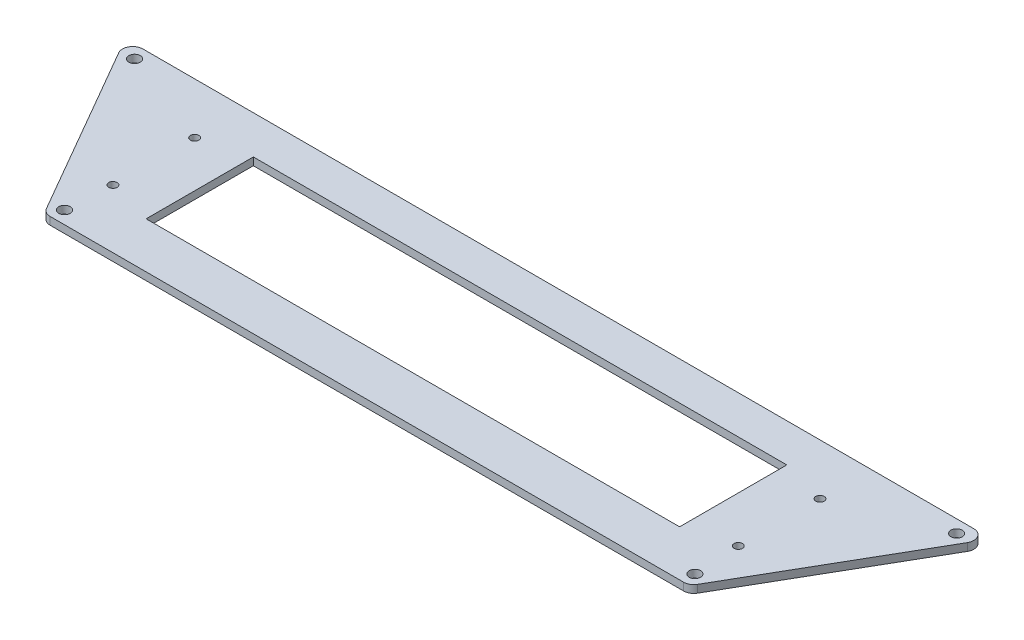
SolidWorks part; units mm, degrees
material "6061 合金"
ref_plane "前视基准面" through (0, 0, 0) normal (0, 0, 1) x (1, 0, 0)
ref_plane "上视基准面" through (0, 0, 0) normal (0, 1, 0) x (1, 0, 0)
ref_plane "右视基准面" through (0, 0, 0) normal (1, 0, 0) x (0, 0, -1)
sketch "草图1" plane through (0, 0, 0) normal (0, 1, 0) x (1, 0, 0)
  line L0 (0, 0) -> (0, 85.8862) construction
  line L1 (-169.688, 36) -> (-126.3868, -39)
  line L2 (-126.3868, -39) -> (126.3868, -39)
  line L3 (169.688, 36) -> (126.3868, -39)
  line L4 (-169.688, 36) -> (169.688, 36)
  line L6 (-161.0278, 31) -> (161.0278, 31) construction
  line L7 (-161.0278, 31) -> (-123.5, -34) construction
  line L8 (-123.5, -34) -> (123.5, -34) construction
  line L9 (161.0278, 31) -> (123.5, -34) construction
  line L10 (-161.0278, 31) -> (123.5, -34) construction
  line L11 (-123.5, -34) -> (161.0278, 31) construction
  line L12 (-122.5, -16) -> (122.5, -16) construction
  line L13 (-122.5, -16) -> (-122.5, 16) construction
  line L14 (-122.5, 16) -> (122.5, 16) construction
  line L15 (122.5, -16) -> (122.5, 16) construction
  line L16 (-122.5, -16) -> (122.5, 16) construction
  line L17 (-122.5, 16) -> (122.5, -16) construction
  point P6 (0, -5.7866)
  dimension "D2" = 5
  dimension "D1" = 15
  dimension "D4" = 247
  dimension "D6" = 32
  dimension "D7" = 245
  dimension "D8" = 18
  dimension "D9" = 120
extrude "凸台-拉伸1" add sketch "草图1" along normal blind 3
hole_wizard "M4 螺纹孔1" positions "草图3" profile "草图2" tap size "M4" standard "GB"
sketch "草图3" plane through (0, 3, 0) normal (0, 1, 0) x (1, 0, 0)
  line L0 (0, 0) -> (0, 124.5937) construction
  point P14 (122.5, 16)
  point P17 (-122.5, -16)
  point P18 (-122.5, 16)
  point P19 (122.5, -16)
sketch "草图2" plane through (122.5, 3, -16) normal (1, 0, 0) x (0, 0, 1)
  line L0 (0, 0) -> (0, 12.4914)
  line L1 (0, 12.4914) -> (1.65, 11.5)
  line L2 (1.65, 11.5) -> (1.65, 0)
  line L5 (1.65, 0) -> (0, 0)
  line L10 (0, 12.4914) -> (-1.65, 11.5) construction
  line L11 (0, -6.35) -> (0, 107.95) construction
  dimension "螺纹孔钻头直径" = 3.3
  dimension "螺纹孔钻头深度" = 11.5
  dimension "导头角度" = 118
cosmetic thread "孔螺蚊线1" parameters "D1"=4, "D2"=4
cosmetic thread "孔螺蚊线3" parameters "D1"=4, "D2"=4
cosmetic thread "孔螺蚊线4" parameters "D1"=4, "D2"=4
cosmetic thread "孔螺蚊线5" parameters "D1"=4, "D2"=4
hole_wizard "M4 间隙孔2" positions "草图8" profile "草图7" hole size "M4" standard "GB"
sketch "草图8" plane through (0, 0, 0) normal (0, -1, 0) x (-1, 0, 0)
  line L0 (0, 0) -> (0, -56.392) construction
  point P0 (-123.5, -34)
  point P2 (123.5, -34)
  point P17 (161.0278, 31)
  point P19 (-161.0278, 31)
sketch "草图7" plane through (123.5, 0, 34) normal (1, 0, 0) x (0, 0, -1)
  line L0 (0, 0) -> (0, 9.3519)
  line L1 (0, 9.3519) -> (2.25, 8)
  line L2 (2.25, 8) -> (2.25, 0)
  line L5 (2.25, 0) -> (0, 0)
  line L10 (0, 9.3519) -> (-2.25, 8) construction
  line L11 (0, -6.35) -> (0, 107.95) construction
  dimension "孔直径" = 4.5
  dimension "孔深度" = 8
  dimension "导头角度" = 118
fillet "圆角1" radius 4 4 edges at (126.3868, 1.5, 39) (169.688, 1.5, -36) (-169.688, 1.5, -36) (-126.3868, 1.5, 39)
sketch "草图9" plane through (0, 0, 0) normal (0, -1, 0) x (1, 0, 0)
  line L0 (0, 0) -> (0, 69.0954) construction
  line L1 (-124.0774, 39) -> (124.0774, 39) construction
  line L2 (-104.5, -21) -> (104.5, -21)
  line L3 (-104.5, -21) -> (-104.5, 21)
  line L4 (-104.5, 21) -> (104.5, 21)
  line L5 (104.5, -21) -> (104.5, 21)
  line L6 (-104.5, -21) -> (104.5, 21) construction
  line L7 (-104.5, 21) -> (104.5, -21) construction
  circle A0 centre (122.5, -16) radius 1.65 construction
  dimension "D1" = 18
  dimension "D2" = 18
extrude "切除-拉伸1" cut sketch "草图9" against normal through all
